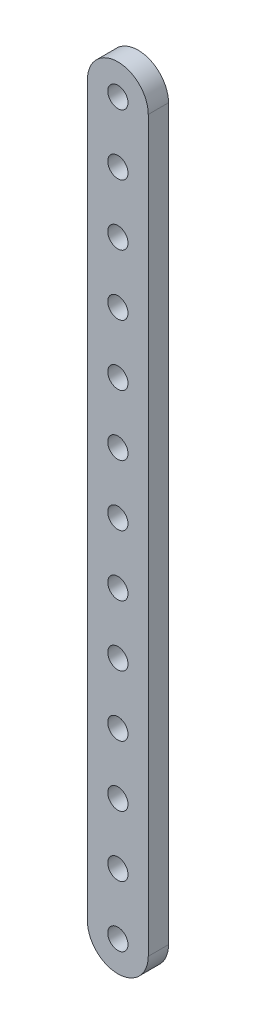
SolidWorks part; units mm, degrees
ref_plane "Alzado" through (0, 0, 0) normal (0, 0, 1) x (1, 0, 0)
ref_plane "Planta" through (0, 0, 0) normal (0, 1, 0) x (1, 0, 0)
ref_plane "Vista lateral" through (0, 0, 0) normal (1, 0, 0) x (0, 0, -1)
sketch "Model" plane through (0, 0, 0) normal (0, 0, 1) x (1, 0, 0)
  line L0 (213.2508, 80.4285) -> (213.2508, 188.4285)
  line L1 (204.2508, 188.4285) -> (204.2508, 80.4285)
  circle A0 centre (208.7508, 179.4285) radius 1.5
  circle A1 centre (208.7508, 188.4285) radius 1.5
  circle A2 centre (208.7508, 152.4285) radius 1.5
  circle A3 centre (208.7508, 161.4285) radius 1.5
  circle A4 centre (208.7508, 170.4285) radius 1.5
  arc A5 (204.2508, 80.4285) -> (213.2508, 80.4285) centre (208.7508, 80.4285) ccw
  arc A6 (213.2508, 188.4285) -> (204.2508, 188.4285) centre (208.7508, 188.4285) ccw
  circle A7 centre (208.7508, 143.4285) radius 1.5
  circle A8 centre (208.7508, 116.4285) radius 1.5
  circle A9 centre (208.7508, 125.4285) radius 1.5
  circle A10 centre (208.7508, 134.4285) radius 1.5
  circle A11 centre (208.7508, 80.4285) radius 1.5
  circle A12 centre (208.7508, 89.4285) radius 1.5
  circle A13 centre (208.7508, 98.4285) radius 1.5
  circle A14 centre (208.7508, 107.4285) radius 1.5
extrude "Saliente-Extruir1" add sketch "Model" along normal blind 3
